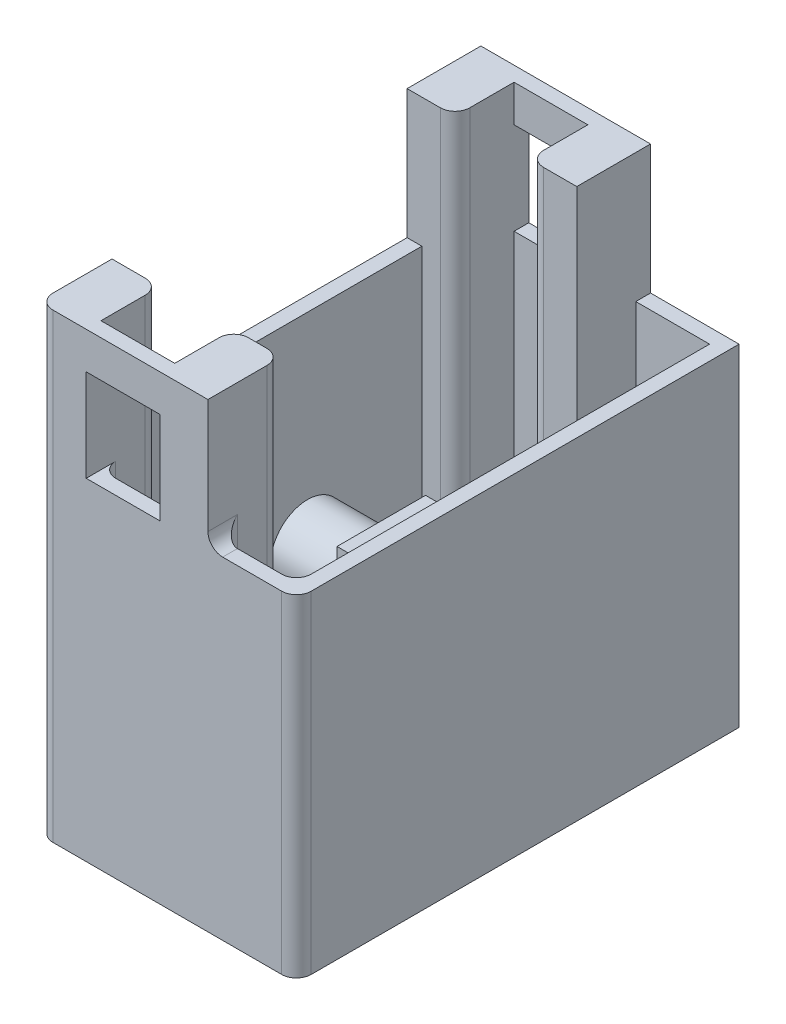
SolidWorks part; units mm, degrees
ref_plane "Front Plane" through (0, 0, 0) normal (1, 0, 0) x (0, 1, 0)
ref_plane "Top Plane" through (0, 0, 0) normal (0, 0, 1) x (0, 1, 0)
ref_plane "Right Plane" through (0, 0, 0) normal (0, 1, 0) x (-1, 0, 0)
sketch "Sketch1" plane through (0, 0, 0) normal (0, 1, 0) x (-1, 0, 0)
  line L0 (15.5, -28) -> (15.5, 28)
  line L1 (-17.5, -30) -> (17.5, -30)
  line L2 (-17.5, -30) -> (-17.5, 30)
  line L3 (-17.5, 30) -> (17.5, 30)
  line L4 (17.5, -30) -> (17.5, 30)
  line L5 (-17.5, -30) -> (17.5, 30) construction
  line L6 (-17.5, 30) -> (17.5, -30) construction
  line L7 (-15.5, 28) -> (15.5, 28)
  line L8 (-15.5, -28) -> (-15.5, 28)
  line L9 (-15.5, -28) -> (15.5, -28)
  point P0 (0, 0)
  dimension "D1" = 35
  dimension "D2" = 60
  dimension "D3" = 2
extrude "Boss-Extrude1" add sketch "Sketch1" along normal blind 45
sketch "Sketch2" plane through (15.5, 0, 0) normal (-1, 0, 0) x (0, -1, 0)
  line L0 (-45, 0) -> (0, 0) construction
  line L1 (-30, -6) -> (0, -6)
  line L2 (-30, -6) -> (-30, 6)
  line L3 (-30, 6) -> (0, 6)
  line L4 (0, -6) -> (0, 6)
  line L5 (-30, -6) -> (0, 6) construction
  line L6 (-30, 6) -> (0, -6) construction
  line L7 (-45, -30) -> (-45, 30) construction
  line L8 (-15, 6) -> (-15, -6) construction
  line L9 (-30, 6) -> (-15, 6) construction
  line L10 (-22.5, 6) -> (-22.5, -6) construction
  point P0 (-15, 0)
  point P12 (-22.5, 0)
  dimension "D1" = 12
  dimension "D2" = 30
extrude "Boss-Extrude2" add sketch "Sketch2" along normal blind 16.5
sketch "Sketch3" plane through (-1, 0, 0) normal (-1, 0, 0) x (0, -1, 0)
  line L0 (-15, 6) -> (-15, -6) construction
  line L1 (-30, 6) -> (-15, 6) construction
  line L2 (-22.5, 6) -> (-22.5, -6) construction
  line L4 (0, -6) -> (0, 6)
  line L5 (0, 6) -> (-30, 6)
  line L6 (-30, 6) -> (-30, -6)
  line L7 (-30, -6) -> (0, -6)
  line L8 (0, -6) -> (0, 6) construction
  line L9 (0, 6) -> (-30, 6) construction
  line L10 (-30, 6) -> (-30, -6) construction
  line L11 (-30, -6) -> (0, -6) construction
  circle A0 centre (-22.5, 0) radius 5
  point P11 (-22.5, 0)
  dimension "D1" = 10
  dimension "D2" = 0
extrude "Boss-Extrude3" add sketch "Sketch3" along normal blind 10
sketch "Sketch4" plane through (0, 45, 0) normal (0, 1, 0) x (-1, 0, 0)
  line L0 (15.5, 28) -> (-15.5, 28) construction
  line L1 (17.5, 30) -> (11, 30)
  line L2 (17.5, 30) -> (17.5, 28)
  line L3 (17.5, 28) -> (11, 28)
  line L4 (11, 30) -> (11, 28)
  line L5 (17.5, 30) -> (-17.5, 30) construction
  line L6 (-5.5, 30) -> (1, 30)
  line L7 (-5.5, 30) -> (-5.5, 28)
  line L8 (-5.5, 28) -> (1, 28)
  line L9 (1, 30) -> (1, 28)
  dimension "D1" = 6.5
  dimension "D2" = 6.5
  dimension "D3" = 10
extrude "Boss-Extrude4" add sketch "Sketch4" along normal blind 17.5
sketch "Sketch5" plane through (-1, 0, 0) normal (-1, 0, 0) x (0, -1, 0)
  line L0 (-62.5, 28) -> (-45, 28) construction
  line L1 (-62.5, 30) -> (-57.5, 30)
  line L2 (-62.5, 30) -> (-62.5, 28)
  line L3 (-62.5, 28) -> (-57.5, 28)
  line L4 (-57.5, 30) -> (-57.5, 28)
  line L5 (-45, -30) -> (-45, 28) construction
  dimension "D1" = 12.5
extrude "Boss-Extrude5" add sketch "Sketch5" along normal up to next
mirror "Mirror1" about plane through (0, 0, 0) normal (0, 0, 1) of "Boss-Extrude4", "Boss-Extrude5"
sketch "Sketch6" plane through (0, 0, 30) normal (0, 0, 1) x (1, 0, 0)
  line L0 (-11, 57.5) -> (-11, 45) construction
  line L2 (-1, 57.5) -> (-1, 45) construction
  line L3 (-11, 57.5) -> (-1, 57.5) construction
  line L4 (-11, 57.5) -> (-11, 45)
  line L6 (-17.5, 0) -> (17.5, 0)
  line L7 (17.5, 0) -> (17.5, 45)
  line L8 (17.5, 45) -> (5.5, 45)
  line L9 (5.5, 45) -> (5.5, 62.5)
  line L10 (5.5, 62.5) -> (-17.5, 62.5)
  line L11 (-17.5, 62.5) -> (-17.5, 0)
  line L15 (5.5, 45) -> (5.5, 62.5)
  line L16 (5.5, 62.5) -> (-17.5, 62.5)
  line L18 (-1, 57.5) -> (-1, 45)
  line L19 (-11, 57.5) -> (-1, 57.5)
  line L20 (-1, 45) -> (5.5, 45)
  line L21 (-17.5, 62.5) -> (-17.5, 45)
  line L22 (-17.5, 45) -> (-11, 45)
  dimension "D1" = 0
sketch "Sketch7" plane through (0, 62.5, 0) normal (0, 1, 0) x (-1, 0, 0)
  line L0 (17.5, 30) -> (-5.5, 30) construction
  line L1 (11, 30) -> (17.5, 30)
  line L2 (11, 30) -> (11, 22)
  line L3 (13, 20) -> (17.5, 20)
  line L4 (17.5, 30) -> (17.5, 20)
  line L5 (17.5, -28) -> (17.5, 28) construction
  line L7 (-5.5, 30) -> (1, 30)
  line L8 (-5.5, 30) -> (-5.5, 20)
  line L9 (-5.5, 20) -> (-1, 20)
  line L10 (1, 30) -> (1, 22)
  arc A0 (11, 22) -> (13, 20) centre (13, 22) ccw
  arc A1 (-1, 20) -> (1, 22) centre (-1, 22) ccw
  dimension "D3" = 2
  dimension "D6" = 2
  dimension "D1" = 6.5
  dimension "D2" = 10
  dimension "D4" = 6.5
  dimension "D5" = 10
extrude "Boss-Extrude6" add sketch "Sketch7" against normal up to surface (62.5 mm away) up to face at (0, 0, 0)
fillet "Fillet1" radius 2 10 edges at (15.5, 22.5, 28) (-17.5, 31.25, 30) (17.5, 22.5, 30) (-11, 22.5, 28) (-1, 22.5, 28) (5.5, 31.25, 20) (5.5, 45, 29) (-16.5, 45, 20) (5.5, 22.5, 28) (-15.5, 22.5, 20)
mirror "Mirror2" about plane through (0, 0, 0) normal (0, 0, 1) of "Boss-Extrude6", "Boss-Extrude4", "Boss-Extrude5"
